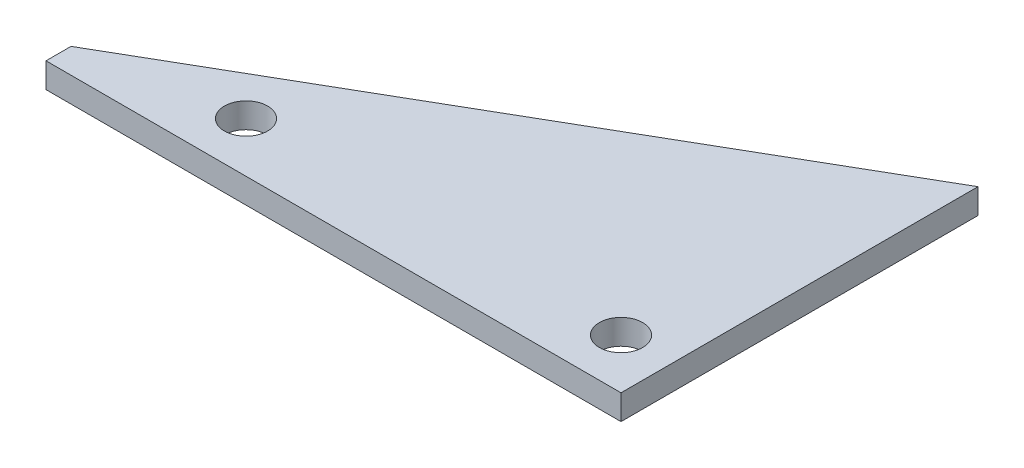
SolidWorks part; units mm, degrees
material "ABS"
ref_plane "Front Plane" through (0, 0, 0) normal (0, 0, 1) x (1, 0, 0)
ref_plane "Top Plane" through (0, 0, 0) normal (0, 1, 0) x (1, 0, 0)
ref_plane "Right Plane" through (0, 0, 0) normal (1, 0, 0) x (0, 0, -1)
sketch "Sketch1" plane through (0, 0, 0) normal (0, 1, 0) x (1, 0, 0)
  line L0 (0, 0) -> (73.025, 0)
  line L1 (73.025, 0) -> (73.025, 45.336)
  line L3 (0, 0) -> (0, 3.175)
  line L4 (0, 3.175) -> (73.025, 45.336)
  dimension "D1" = 73.025
  dimension "D2" = 3.175
  dimension "D3" = 30
extrude "Boss-Extrude1" add sketch "Sketch1" along normal blind 3.175
sketch "Sketch2" plane through (0, 3.175, 0) normal (0, 1, 0) x (1, 0, 0)
  line L0 (0, 3.175) -> (0, 0) construction
  line L1 (0, 0) -> (73.025, 0) construction
  line L2 (73.025, 0) -> (73.025, 45.336) construction
  point P0 (19.05, 6.35)
  point P1 (66.675, 6.35)
  dimension "D1" = 19.05
  dimension "D2" = 6.35
  dimension "D3" = 6.35
  dimension "D4" = 6.35
hole_wizard "M5 Clearance Hole1" positions "Sketch3" profile "Sketch4" hole size "M5" standard "ANSI Metric" end condition through all
sketch "Sketch3" plane through (0, 3.175, 0) normal (0, 1, 0) x (1, 0, 0)
  point P0 (19.05, 6.35)
  point P3 (66.675, 6.35)
sketch "Sketch4" plane through (19.05, 3.175, -6.35) normal (1, 0, 0) x (0, 0, 1)
  line L0 (0, 0) -> (0, 3.175)
  line L1 (0, 3.175) -> (2.75, 3.175)
  line L2 (2.75, 3.175) -> (2.75, 0)
  line L5 (2.75, 0) -> (0, 0)
  line L11 (0, -6.35) -> (0, 107.95) construction
  dimension "Thru Hole Dia." = 5.5
  dimension "Thru Hole Depth" = 3.175
